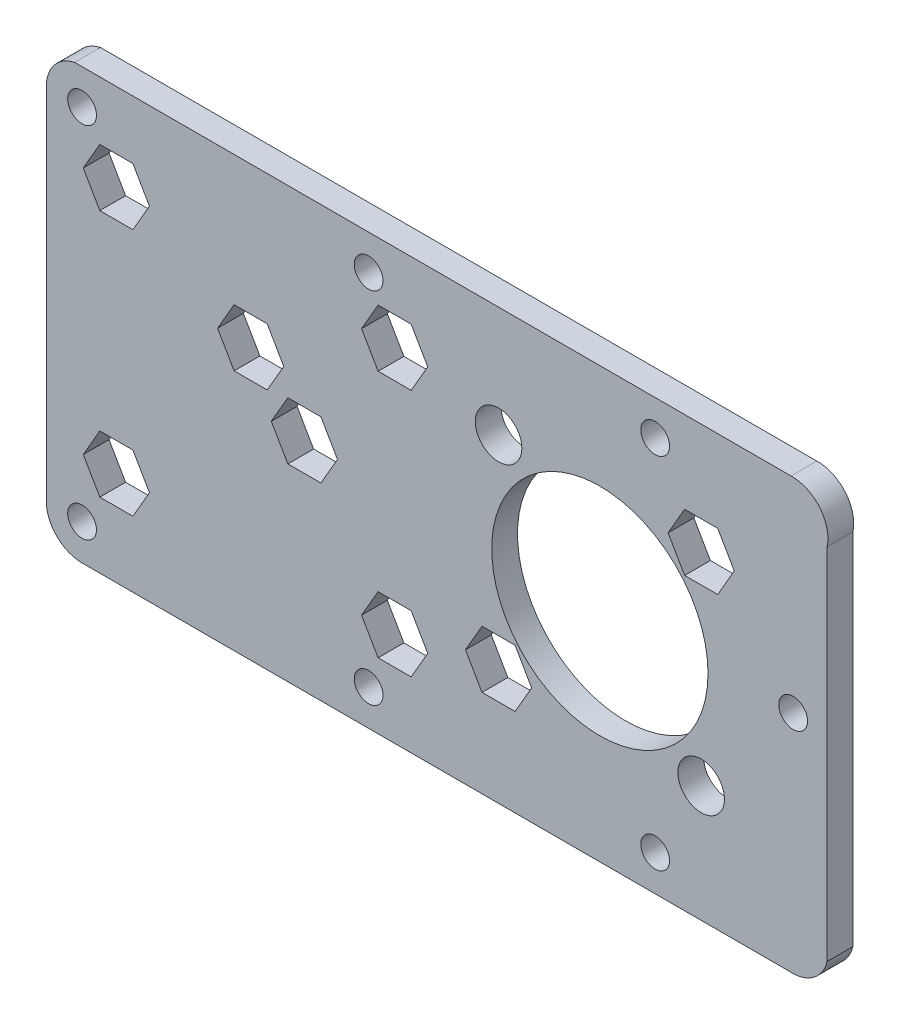
SolidWorks part; units mm, degrees
ref_plane "Front Plane" through (0, 0, 0) normal (0, 0, 1) x (1, 0, 0)
ref_plane "Top Plane" through (0, 0, 0) normal (0, 1, 0) x (1, 0, 0)
ref_plane "Right Plane" through (0, 0, 0) normal (1, 0, 0) x (0, 0, -1)
sketch "Sketch1" plane through (0, 0, 0) normal (0, 0, 1) x (1, 0, 0)
  line L1 (-17.186, 5.9175) -> (-17.186, 69.5621)
  line L2 (121.2511, 68.0593) -> (121.2511, 4.4147)
  line L6 (-12.1554, 75.7735) -> (114.8578, 75.7735)
  line L7 (-11.1125, -0.4265) -> (114.4874, -0.4265)
  line L10 (1.1034, 60.325) -> (-1.8296, 65.405)
  line L11 (-1.8296, 65.405) -> (-7.6954, 65.405)
  line L12 (-7.6954, 65.405) -> (-10.6284, 60.325)
  line L13 (-10.6284, 60.325) -> (-7.6954, 55.245)
  line L14 (-7.6954, 55.245) -> (-1.8296, 55.245)
  line L15 (-1.8296, 55.245) -> (1.1034, 60.325)
  line L16 (50.4432, 60.325) -> (47.5103, 65.405)
  line L17 (47.5103, 65.405) -> (41.6444, 65.405)
  line L18 (41.6444, 65.405) -> (38.7115, 60.325)
  line L19 (38.7115, 60.325) -> (41.6444, 55.245)
  line L20 (41.6444, 55.245) -> (47.5103, 55.245)
  line L21 (47.5103, 55.245) -> (50.4432, 60.325)
  line L22 (1.1034, 16.3313) -> (-1.8296, 21.4113)
  line L23 (-1.8296, 21.4113) -> (-7.6954, 21.4113)
  line L24 (-7.6954, 21.4113) -> (-10.6284, 16.3313)
  line L25 (-10.6284, 16.3313) -> (-7.6954, 11.2513)
  line L26 (-7.6954, 11.2513) -> (-1.8296, 11.2513)
  line L27 (-1.8296, 11.2513) -> (1.1034, 16.3313)
  line L28 (50.4432, 16.3313) -> (47.5103, 21.4113)
  line L29 (47.5103, 21.4113) -> (41.6444, 21.4113)
  line L30 (41.6444, 21.4113) -> (38.7115, 16.3313)
  line L31 (38.7115, 16.3313) -> (41.6444, 11.2513)
  line L32 (41.6444, 11.2513) -> (47.5103, 11.2513)
  line L33 (47.5103, 11.2513) -> (50.4432, 16.3313)
  line L34 (68.8679, 20.2308) -> (65.9349, 25.3108)
  line L35 (65.9349, 25.3108) -> (60.069, 25.3108)
  line L36 (60.069, 25.3108) -> (57.1361, 20.2308)
  line L37 (57.1361, 20.2308) -> (60.069, 15.1508)
  line L38 (60.069, 15.1508) -> (65.9349, 15.1508)
  line L39 (65.9349, 15.1508) -> (68.8679, 20.2308)
  line L40 (104.7889, 56.1518) -> (101.856, 61.2318)
  line L41 (101.856, 61.2318) -> (95.9901, 61.2318)
  line L42 (95.9901, 61.2318) -> (93.0571, 56.1518)
  line L43 (93.0571, 56.1518) -> (95.9901, 51.0718)
  line L44 (95.9901, 51.0718) -> (101.856, 51.0718)
  line L45 (101.856, 51.0718) -> (104.7889, 56.1518)
  line L46 (24.9159, 47.625) -> (21.9829, 52.705)
  line L47 (21.9829, 52.705) -> (16.1171, 52.705)
  line L48 (16.1171, 52.705) -> (13.1841, 47.625)
  line L49 (13.1841, 47.625) -> (16.1171, 42.545)
  line L50 (16.1171, 42.545) -> (21.9829, 42.545)
  line L51 (21.9829, 42.545) -> (24.9159, 47.625)
  line L52 (34.4409, 38.1) -> (31.5079, 43.18)
  line L53 (31.5079, 43.18) -> (25.6421, 43.18)
  line L54 (25.6421, 43.18) -> (22.7091, 38.1)
  line L55 (22.7091, 38.1) -> (25.6421, 33.02)
  line L56 (25.6421, 33.02) -> (31.5079, 33.02)
  line L57 (31.5079, 33.02) -> (34.4409, 38.1)
  circle A0 centre (90.764, 5.9175) radius 2.5527
  circle A1 centre (90.764, 69.5621) radius 2.5527
  circle A2 centre (-4.7625, 60.325) radius 5.08 construction
  arc A3 (-17.186, 69.5621) -> (-12.1554, 75.7735) centre (-10.836, 69.5621) cw
  arc A4 (-17.186, 5.9175) -> (-11.1125, -0.4265) centre (-10.836, 5.9175) ccw
  arc A5 (114.4874, -0.4265) -> (121.2511, 4.4147) centre (115.0763, 5.8961) ccw
  arc A6 (114.8578, 75.7735) -> (121.2511, 68.0593) centre (115.05, 69.4264) cw
  circle A8 centre (-10.836, 69.5621) radius 2.5527
  circle A9 centre (-4.7625, 60.325) radius 2.5527
  circle A13 centre (39.964, 69.5621) radius 2.5527
  circle A14 centre (44.5773, 60.325) radius 2.5527
  circle A15 centre (19.05, 47.625) radius 2.5527
  circle A16 centre (28.575, 38.1) radius 2.5527
  circle A18 centre (-4.7625, 16.3313) radius 2.5527
  circle A19 centre (-10.836, 5.9175) radius 2.5527
  circle A23 centre (44.5773, 16.3313) radius 2.5527
  circle A24 centre (39.964, 5.9175) radius 2.5527
  circle A25 centre (63.002, 20.2308) radius 2.5527
  circle A26 centre (63.002, 56.1518) radius 4.1275
  circle A27 centre (98.923, 56.1518) radius 2.5527
  circle A28 centre (115.2331, 39.5816) radius 2.5527
  circle A29 centre (98.923, 20.2308) radius 4.1275
  circle A30 centre (80.9625, 38.1) radius 19.177
  circle A31 centre (44.5773, 60.325) radius 5.08 construction
  circle A32 centre (-4.7625, 16.3313) radius 5.08 construction
  circle A33 centre (44.5773, 16.3313) radius 5.08 construction
  circle A34 centre (63.002, 20.2308) radius 5.08 construction
  circle A35 centre (98.923, 56.1518) radius 5.08 construction
  circle A36 centre (19.05, 47.625) radius 5.08 construction
  circle A37 centre (28.575, 38.1) radius 5.08 construction
  dimension "D3" = 6.35
  dimension "D4" = 5.1054
  dimension "D6" = 50.8
  dimension "D1" = 138.4371
  dimension "D2" = 76.2
  dimension "D5" = 50.8
  dimension "D7" = 35.921
  dimension "D8" = 35.921
  dimension "D9" = 17.9605
  dimension "D10" = 18.0518
  dimension "D11" = 10.16
extrude "Boss-Extrude1" add sketch "Sketch1" along normal blind 4.572 contours A6 L6 A3 L1 A4 L7 A5 L2 A30 A29 A28 A26 A24 A19 A13 A8 A1 A0 L57 L56 L55 L54 L53 L52 L51 L50 L49 L48 L47 L46 L45 L44 L43 L42 L41 L40 L39
